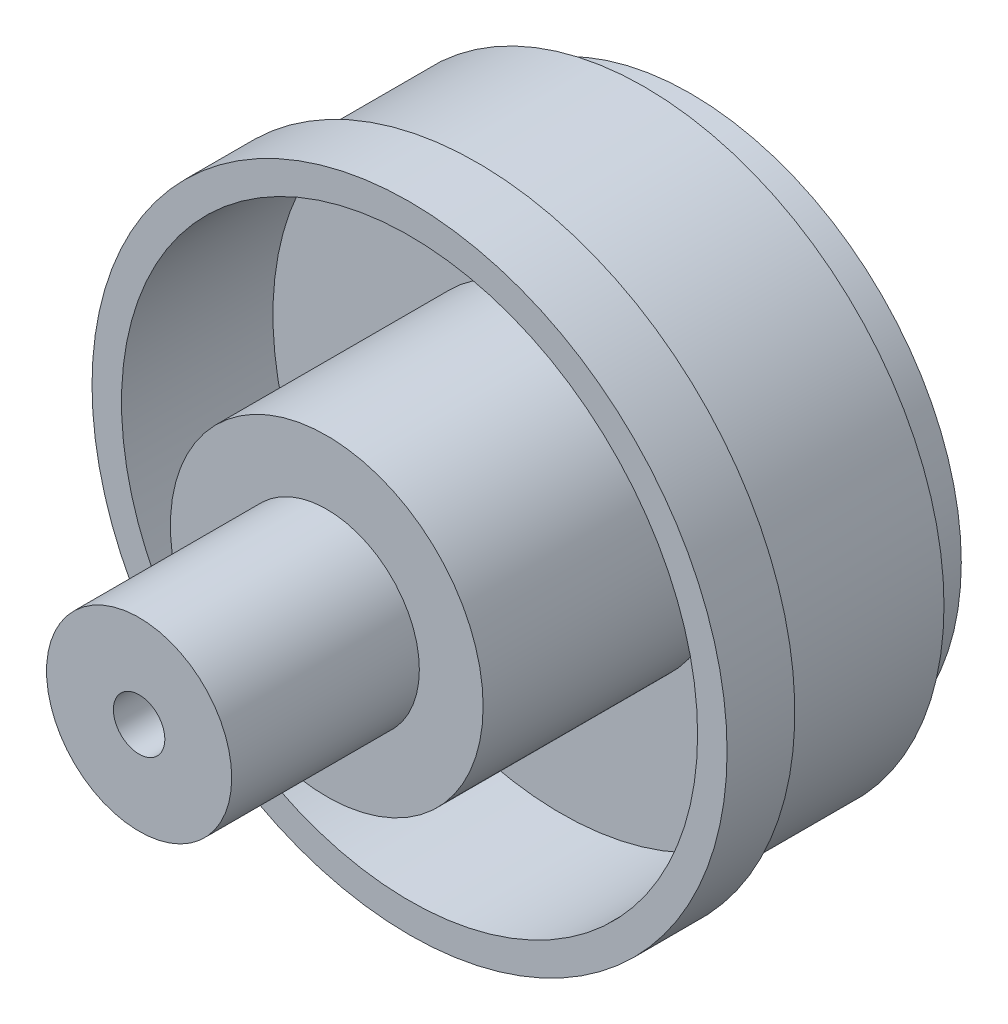
SolidWorks part; units mm, degrees
material "6061-T6 (SS)"
ref_plane "Front Plane" through (0, 0, 0) normal (0, 0, 1) x (1, 0, 0)
ref_plane "Top Plane" through (0, 0, 0) normal (0, 1, 0) x (1, 0, 0)
ref_plane "Right Plane" through (0, 0, 0) normal (1, 0, 0) x (0, 0, -1)
sketch "Sketch1" plane through (0, 0, 0) normal (0, 0, 1) x (1, 0, 0)
  circle A0 centre (0, 0) radius 49
extrude "Extrude1" add sketch "Sketch1" along normal blind 85.09
sketch "Sketch5" plane through (0, 0, 85.09) normal (0, 0, 1) x (1, 0, 0)
  circle A0 centre (0, 0) radius 3.9688
extrude "Extrude5" cut sketch "Sketch5" against normal blind 26.67
sketch "Sketch2" plane through (0, 0, 85.09) normal (0, 0, 1) x (1, 0, 0)
  circle A0 centre (0, 0) radius 14.2875
extrude "Extrude2" cut sketch "Sketch2" against normal blind 28.956 flip side to cut
sketch "Sketch3" plane through (0, 0, 56.134) normal (0, 0, 1) x (1, 0, 0)
  circle A0 centre (0, 0) radius 24.13
extrude "Extrude3" cut sketch "Sketch3" against normal blind 12.7762 flip side to cut
sketch "Sketch4" plane through (0, 0, 0) normal (0, 0, -1) x (-1, 0, 0)
  circle A0 centre (0, 0) radius 46.228
extrude "Extrude4" cut sketch "Sketch4" against normal blind 32.9057 flip side to cut
sketch "Sketch6" plane through (0, 0, 43.3578) normal (0, 0, 1) x (1, 0, 0)
  circle A0 centre (0, 0) radius 44.45
  circle A1 centre (0, 0) radius 24.13
extrude "Extrude8" cut sketch "Sketch6" against normal blind 23.368
sketch "Sketch7" plane through (0, 0, 0) normal (0, 0, -1) x (-1, 0, 0)
  circle A0 centre (0, 0) radius 19.05
extrude "Extrude9" cut sketch "Sketch7" against normal blind 50.8
sketch "Sketch8" plane through (0, 0, 0) normal (0, 0, -1) x (-1, 0, 0)
  circle A0 centre (0, 0) radius 41.783
extrude "Extrude10" cut sketch "Sketch8" against normal blind 7.112 flip side to cut
